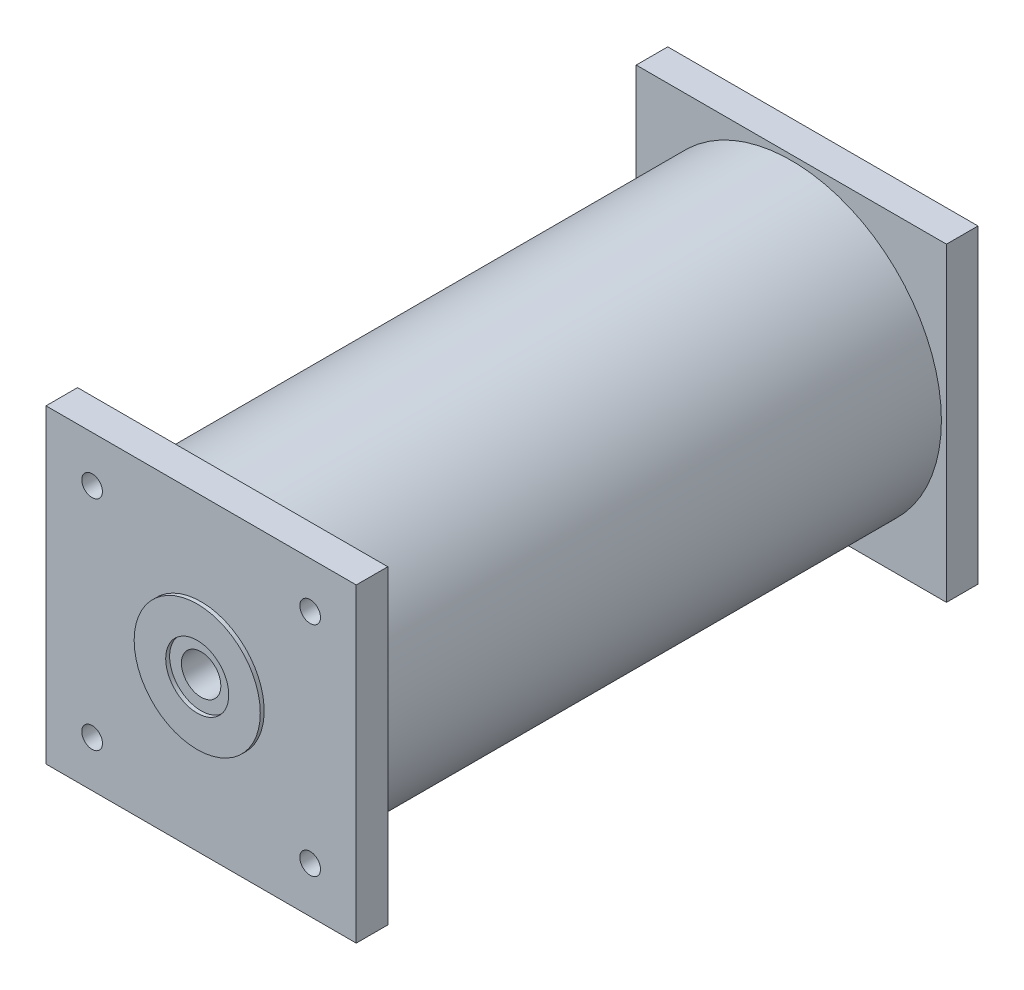
SolidWorks part; units mm, degrees
ref_plane "Frontal Plane" through (0, 0, 0) normal (0, 0, 1) x (1, 0, 0)
ref_plane "Horizontal Plane" through (0, 0, 0) normal (0, 1, 0) x (1, 0, 0)
ref_plane "Profile Plane" through (0, 0, 0) normal (1, 0, 0) x (0, 0, -1)
sketch "Sketch1" plane through (0, 0, 0) normal (1, 0, 0) x (0, 0, -1)
  line L2 (0, 0) -> (0, -30.225)
  line L3 (0, -30.225) -> (112.522, -30.225)
  line L4 (112.522, -30.225) -> (112.522, 0)
  line L6 (-17.5883, 0) -> (102.2274, 0) construction
  line L10 (0, 0) -> (112.522, 0)
  dimension "D3" = 30.225
  dimension "D1" = 112.522
revolve "Revolve1" add sketch "Sketch1" angle 360 about L6
ref_plane "Plane1" through (0, 0, 0) normal (0, 0, 1) x (1, 0, 0)
sketch "Sketch2" plane through (0, 0, 0) normal (0, 0, 1) x (1, 0, 0)
  line L1 (-31.242, -31.242) -> (31.242, -31.242)
  line L2 (-31.242, -31.242) -> (-31.242, 31.242)
  line L3 (-31.242, 31.242) -> (31.242, 31.242)
  line L4 (31.242, -31.242) -> (31.242, 31.242)
  line L5 (-31.242, -31.242) -> (31.242, 31.242) construction
  line L6 (-31.242, 31.242) -> (31.242, -31.242) construction
  circle A0 centre (0, 0) radius 3.9688
  point P0 (0, 0)
  dimension "D3" = 7.9375
  dimension "D1" = 62.484
  dimension "D2" = 62.484
extrude "Boss-Extrude1" add sketch "Sketch2" along normal blind 6.35
sketch "Sketch3" plane through (0, 0, 0) normal (0, 0, 1) x (1, 0, 0)
  circle A0 centre (0, 0) radius 6.35
  circle A1 centre (0, 0) radius 12.7
  dimension "D1" = 25.4
  dimension "D2" = 12.7
extrude "Boss-Extrude2" add sketch "Sketch3" along normal blind 7.1374
ref_plane "Plane2" through (0, 0, -112.522) normal (0, 0, -1) x (-1, 0, 0)
sketch "Sketch4" plane through (0, 0, -112.522) normal (0, 0, -1) x (-1, 0, 0)
  line L1 (-31.242, -31.242) -> (31.242, -31.242)
  line L2 (-31.242, -31.242) -> (-31.242, 31.242)
  line L3 (-31.242, 31.242) -> (31.242, 31.242)
  line L4 (31.242, -31.242) -> (31.242, 31.242)
  line L5 (-31.242, -31.242) -> (31.242, 31.242) construction
  line L6 (-31.242, 31.242) -> (31.242, -31.242) construction
  point P0 (0, 0)
extrude "Boss-Extrude3" add sketch "Sketch4" along normal blind 6.35
sketch "Sketch5" plane through (0, -31.242, 0) normal (0, -1, 0) x (1, 0, 0)
  line L0 (-31.242, 6.35) -> (-31.242, 0) construction
  line L1 (-15.875, 3.175) -> (15.875, 3.175) construction
  circle A0 centre (-15.875, 3.175) radius 2.0828
  circle A1 centre (15.875, 3.175) radius 2.0828
  point P4 (0, 3.175)
  point P7 (-31.242, 3.175)
  dimension "D1" = 4.1656
  dimension "D2" = 15.875
extrude "Cut-Extrude1" cut sketch "Sketch5" against normal blind 8.255
pattern_linear "LPattern1" count 2 spacing 118.872 along (0, 0, -1) of "Cut-Extrude1"
sketch "Sketch6" plane through (0, 0, 6.35) normal (0, 0, 1) x (1, 0, 0)
  circle A0 centre (21.9583, -21.9583) radius 2.0828
  dimension "D3" = 4.1656
  dimension "D1" = 21.9583
  dimension "D2" = 21.9583
extrude "Cut-Extrude2" cut sketch "Sketch6" against normal blind 6.35
pattern_linear "LPattern2" count 2 spacing 43.9166 along (0, 1, 0) count 2 spacing 43.9166 along (-1, 0, 0) of "Cut-Extrude2"
equation "\"BaseL\"= 6ft"
equation "\"BaseW\"= 5.5in"
equation "\"BaseThickness\"= 1in"
equation "\"RailGap\"= 4cm"
equation "\"SlidePlateL\"= 8cm"
equation "\"SlidePlateW\"= 11cm"
equation "\"SlidePlateThickness\"= 5mm"
equation "\"SlidePlateClearance\"= 1cm"
equation "\"BoxThickness\"= .5cm"
equation "\"BoxX\"= \"RailGap\" + 30mm"
equation "\"BoxH\"= 2cm + \"SlidePlateClearance\" + \"SlidePlateThickness\" + 3cm"
equation "\"BeltW\"= .375in"
equation "\"PulleyRadius\"= 15.1mm"
equation "\"PulleyH\"= 30mm + 21.4056mm - 2.5mm"
equation "\"PulleyShaftDiameter\"= .3125in"
equation "\"PulleyShaftL\"= 4in"
equation "\"MotorL\"= 4.43in"
equation "\"MotorRadius\"= 1.291in"
equation "\"MotorShaftRadius\"= .15625in"
equation "\"D1@Sketch1\"=\"MotorL\""
equation "\"PulleyShaft2L\"= 3in"
equation "\"MotorShaftL\"= 1.75in"
equation "\"HeadstoneThickness\"= 7.5mm"
equation "\"BeltL\"= 1500mm + \"80\""
equation "\"BeltThickness\"= 2.5mm"
equation "\"BeltLockH\"= \"PulleyH\" + 19.4056mm - (\"SlidePlateThickness\" + \"SlidePlateClearance\" + 15mm + 5mm)"
equation "\"EncoderL\"= 33mm"
equation "\"EncoderRadius\"= 19mm"
equation "\"EncoderShaftRadius\"= 3mm"
equation "\"EncoderShaftL\"= 15mm"
equation "\"PendulumShaftL\"= \"100mm\" "
equation "\"PendulumShaftRadius\"= 3mm"
equation "\"RodL\"= 39in"
equation "\"RodRadius\"= 3mm"
equation "\"PillowBlockCenterH\"= \"EncoderRadius\" + 2mm"
equation "\"D2@Sketch1\"=\"MotorShaft\""
equation "\"MotorPlateX\" = 2.582in"
